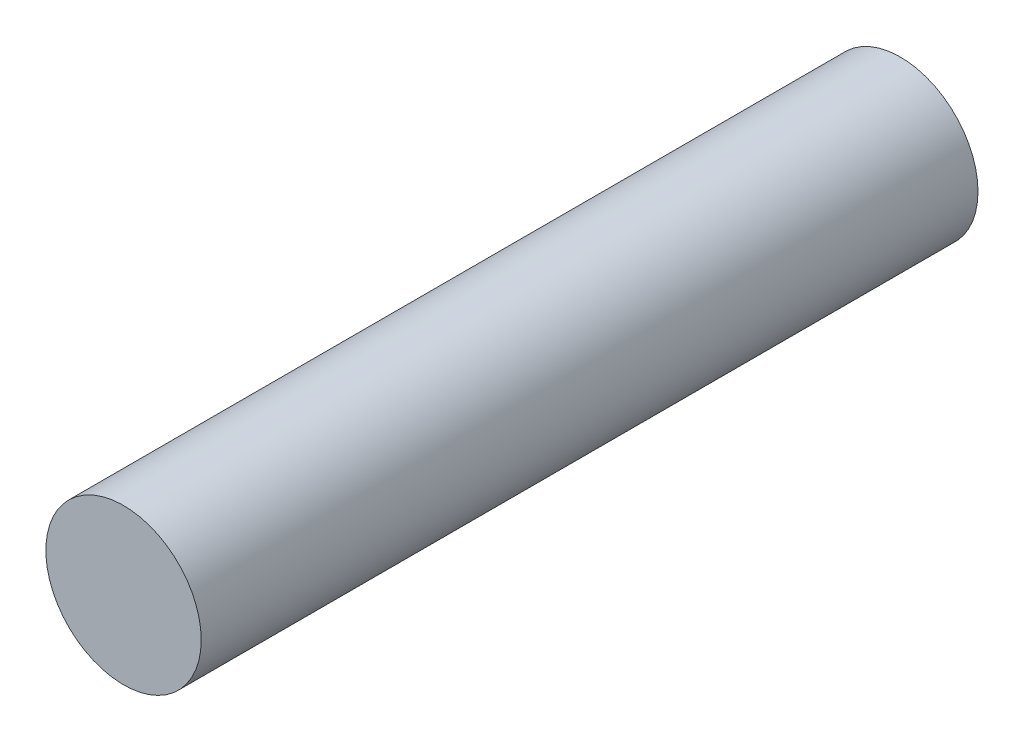
SolidWorks part; units mm, degrees
ref_plane "Front Plane" through (0, 0, 0) normal (0, 0, 1) x (1, 0, 0)
ref_plane "Top Plane" through (0, 0, 0) normal (0, 1, 0) x (1, 0, 0)
ref_plane "Right Plane" through (0, 0, 0) normal (1, 0, 0) x (0, 0, -1)
sketch "Sketch2" plane through (0, 0, 0) normal (0, 0, 1) x (1, 0, 0)
  circle A0 centre (0, 0) radius 5
  dimension "D1" = 10
extrude "Boss-Extrude1" add sketch "Sketch2" against normal blind 50
